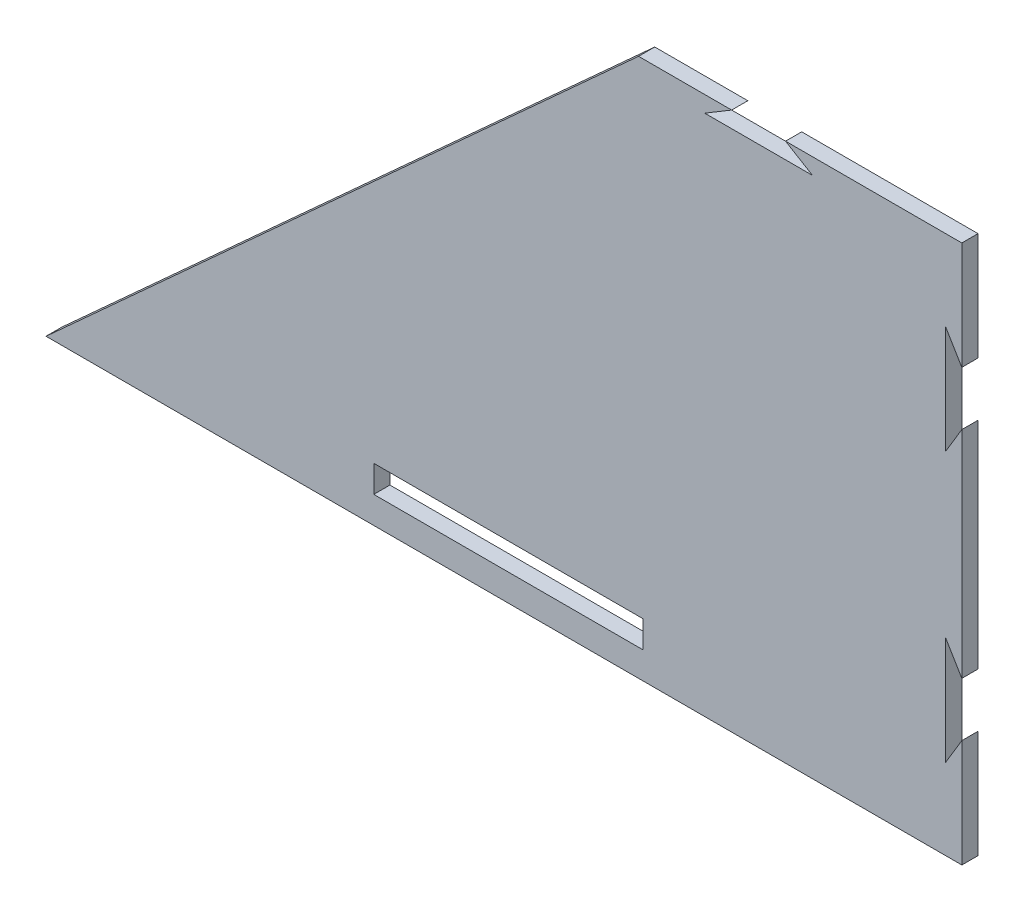
SolidWorks part; units mm, degrees
ref_plane "Plan de face" through (0, 0, 0) normal (0, 0, 1) x (1, 0, 0)
ref_plane "Plan de dessus" through (0, 0, 0) normal (0, 1, 0) x (1, 0, 0)
ref_plane "Plan de droite" through (0, 0, 0) normal (1, 0, 0) x (0, 0, -1)
sketch "Esquisse1" plane through (0, 0, 0) normal (0, 0, 1) x (1, 0, 0)
  line L0 (-78.2721, -71.9753) -> (31.7279, 28.0247)
  line L1 (-78.2721, -71.9753) -> (91.7279, -71.9753)
  line L3 (31.7279, 28.0247) -> (91.7279, 28.0247)
  line L4 (91.7279, -71.9753) -> (91.7279, 28.0247)
  point P0 (0, 0)
  dimension "D1" = 60
  dimension "D2" = 100
  dimension "D3" = 170
extrude "Boss.-Extru.1" add sketch "Esquisse1" along normal blind 3
sketch "Esquisse2" plane through (0, 0, 3) normal (0, 0, 1) x (1, 0, 0)
  line L0 (49.0021, 28.0247) -> (44.0021, 25.0247)
  line L1 (91.7279, 28.0247) -> (31.7279, 28.0247) construction
  line L2 (44.0021, 25.0247) -> (64.0021, 25.0247)
  line L3 (64.0021, 25.0247) -> (59.0021, 28.0247)
  dimension "D1" = 20
  dimension "D2" = 10
  dimension "D3" = 3
  dimension "D4" = 5
extrude "Enlèv. mat.-Extru.1" cut sketch "Esquisse2" against normal blind 3 and the other way through all
sketch "Esquisse3" plane through (0, 0, 3) normal (0, 0, 1) x (1, 0, 0)
  line L0 (91.7279, 8.0247) -> (88.7279, 13.0247)
  line L1 (91.7279, -71.9753) -> (91.7279, 28.0247) construction
  line L2 (88.7279, 13.0247) -> (88.7279, -6.9753)
  line L3 (88.7279, -6.9753) -> (91.7279, -1.9753)
  line L4 (91.7279, -41.9753) -> (88.7279, -36.9753)
  line L5 (88.7279, -36.9753) -> (88.7279, -56.9753)
  line L6 (88.7279, -56.9753) -> (91.7279, -51.9753)
  line L7 (91.7279, 8.0247) -> (91.7279, -1.9753)
  line L8 (91.7279, -41.9753) -> (91.7279, -51.9753)
  dimension "D1" = 10
  dimension "D2" = 5
  dimension "D3" = 20
  dimension "D4" = 20
  dimension "D5" = 20
  dimension "D6" = 10
  dimension "D7" = 5
  dimension "D8" = 3
  dimension "D9" = 3
  dimension "D10" = 40
extrude "Enlèv. mat.-Extru.2" cut sketch "Esquisse3" against normal blind 3
sketch "Esquisse4" plane through (0, 0, 3) normal (0, 0, 1) x (1, 0, 0)
  line L0 (-78.2721, -71.9753) -> (91.7279, -71.9753) construction
  line L1 (-17.4312, -61.9753) -> (32.5688, -61.9753)
  line L2 (-17.4312, -61.9753) -> (-17.4312, -66.9753)
  line L3 (-17.4312, -66.9753) -> (32.5688, -66.9753)
  line L4 (32.5688, -61.9753) -> (32.5688, -66.9753)
  line L5 (-17.4312, -61.9753) -> (32.5688, -66.9753) construction
  line L6 (-17.4312, -66.9753) -> (32.5688, -61.9753) construction
  point P0 (7.5688, -64.4753)
  dimension "D1" = 5
  dimension "D2" = 50
  dimension "D3" = 5
extrude "Enlèv. mat.-Extru.3" cut sketch "Esquisse4" against normal blind 3
